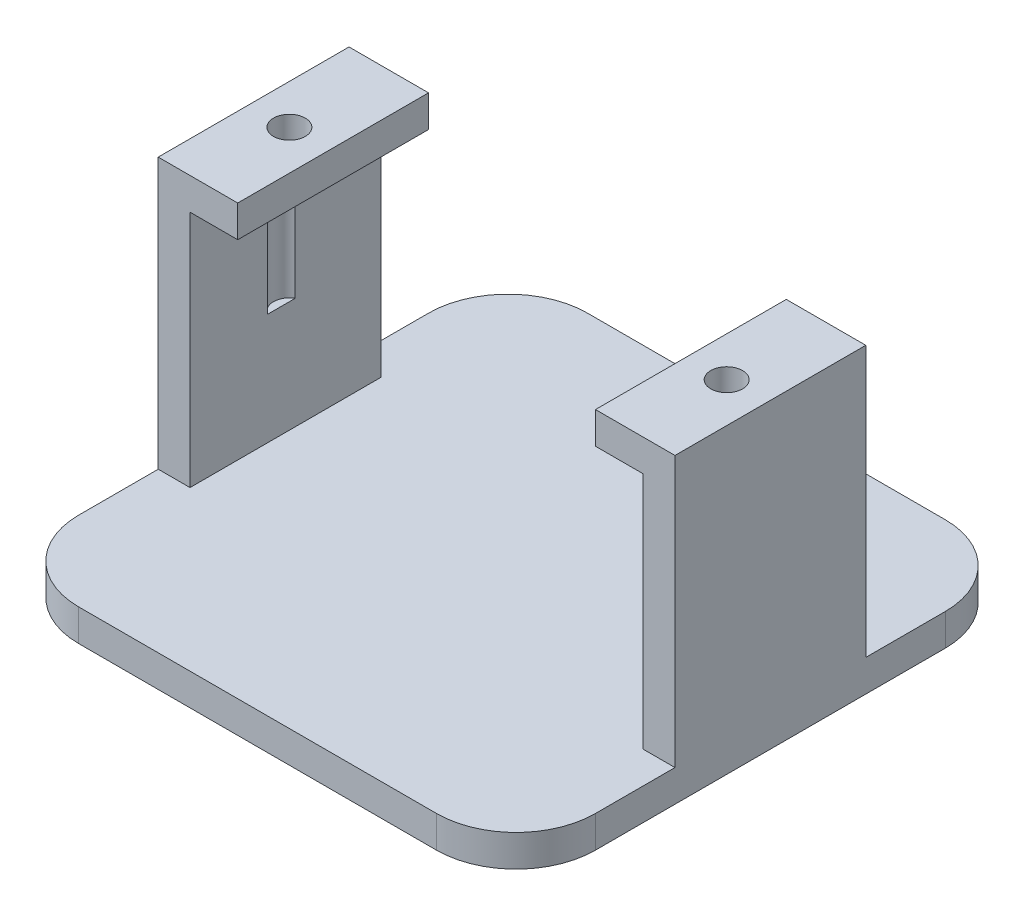
SolidWorks part; units mm, degrees
material "ABS"
ref_plane "Front Plane" through (0, 0, 0) normal (0, 0, 1) x (1, 0, 0)
ref_plane "Top Plane" through (0, 0, 0) normal (0, 1, 0) x (1, 0, 0)
ref_plane "Right Plane" through (0, 0, 0) normal (1, 0, 0) x (0, 0, -1)
sketch "Sketch1" plane through (0, 0, 0) normal (0, 1, 0) x (1, 0, 0)
  line L1 (0, 0) -> (32.5, 0)
  line L2 (0, 0) -> (0, 12)
  line L3 (0, 12) -> (32.5, 12)
  line L4 (32.5, 0) -> (32.5, 12)
  dimension "D1" = 32.5
  dimension "D2" = 12
extrude "Boss-Extrude1" add sketch "Sketch1" along normal blind 2
sketch "Sketch2" plane through (0, 2, 0) normal (0, 1, 0) x (1, 0, 0)
  line L0 (32.5, 12) -> (0, 12) construction
  line L1 (0, 0) -> (2, 0)
  line L2 (0, 0) -> (0, 12)
  line L3 (0, 12) -> (2, 12)
  line L4 (2, 0) -> (2, 12)
  line L6 (32.5, 0) -> (30.5, 0)
  line L7 (32.5, 0) -> (32.5, 12)
  line L8 (32.5, 12) -> (30.5, 12)
  line L9 (30.5, 0) -> (30.5, 12)
  dimension "D1" = 2
  dimension "D2" = 2
extrude "Boss-Extrude2" add sketch "Sketch2" along normal blind 17
sketch "Sketch3" plane through (2, 0, 0) normal (1, 0, 0) x (0, 0, -1)
  line L0 (12, 19) -> (12, 2) construction
  line L1 (0, 19) -> (12, 19)
  line L2 (0, 19) -> (0, 17)
  line L3 (0, 17) -> (12, 17)
  line L4 (12, 19) -> (12, 17)
  dimension "D1" = 2
extrude "Boss-Extrude3" add sketch "Sketch3" along normal blind 3
sketch "Sketch4" plane through (30.5, 0, 0) normal (-1, 0, 0) x (0, 0, 1)
  line L0 (0, 19) -> (0, 2) construction
  line L1 (-12, 19) -> (0, 19)
  line L2 (-12, 19) -> (-12, 17)
  line L3 (-12, 17) -> (0, 17)
  line L4 (0, 19) -> (0, 17)
  dimension "D1" = 2
extrude "Boss-Extrude4" add sketch "Sketch4" along normal blind 3
sketch "Sketch5" plane through (0, 0, -12) normal (0, 0, -1) x (-1, 0, 0)
  line L0 (-32.5, 19) -> (-32.5, 0) construction
  line L1 (-32.5, 2) -> (0, 2)
  line L2 (-32.5, 2) -> (-32.5, 0)
  line L3 (-32.5, 0) -> (0, 0)
  line L4 (0, 2) -> (0, 0)
extrude "Boss-Extrude6" add sketch "Sketch5" along normal blind 10
sketch "Sketch7" plane through (0, 0, 0) normal (0, 0, 1) x (1, 0, 0)
  line L0 (0, 19) -> (0, 0) construction
  line L1 (0, 2) -> (32.5, 2)
  line L2 (0, 2) -> (0, 0)
  line L3 (0, 0) -> (32.5, 0)
  line L4 (32.5, 2) -> (32.5, 0)
extrude "Boss-Extrude7" add sketch "Sketch7" along normal blind 10
fillet "Fillet1" radius 5 4 edges at (32.5, 1, 10) (0, 1, 10) (32.5, 1, -22) (0, 1, -22)
sketch "Sketch8" plane through (0, 19, 0) normal (0, 1, 0) x (1, 0, 0)
  circle A0 centre (2.5, 5.75) radius 1
  circle A1 centre (30, 5.75) radius 1
extrude "Cut-Extrude1" cut sketch "Sketch8" against normal blind 10
